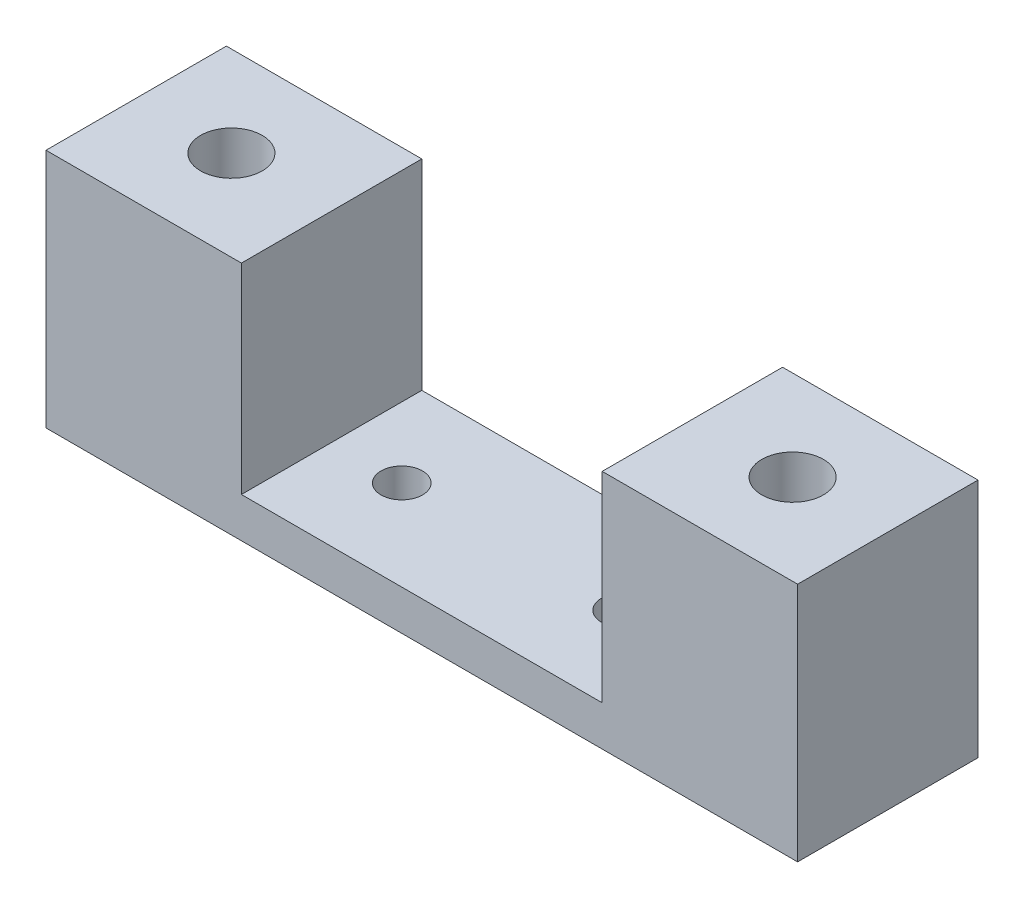
SolidWorks part; units mm, degrees
ref_plane "Front Plane" through (0, 0, 0) normal (0, 0, 1) x (1, 0, 0)
ref_plane "Top Plane" through (0, 0, 0) normal (0, 1, 0) x (1, 0, 0)
ref_plane "Right Plane" through (0, 0, 0) normal (1, 0, 0) x (0, 0, -1)
sketch "Sketch1" plane through (0, 0, 0) normal (0, 1, 0) x (1, 0, 0)
  line L1 (0, 0) -> (75, 0)
  line L2 (0, 0) -> (0, -18)
  line L3 (0, -18) -> (75, -18)
  line L4 (75, 0) -> (75, -18)
  dimension "D1" = 18
  dimension "D2" = 75
extrude "Boss-Extrude1" add sketch "Sketch1" along normal blind 24
sketch "Sketch2" plane through (0, 24, 0) normal (0, 1, 0) x (1, 0, 0)
  line L0 (0, 0) -> (19.5, 0) construction
  line L1 (75, 0) -> (0, 0) construction
  line L2 (0, -18) -> (75, -18) construction
  line L3 (19.5, 0) -> (55.5, 0)
  line L4 (19.5, 0) -> (19.5, -18)
  line L5 (19.5, -18) -> (55.5, -18)
  line L6 (55.5, 0) -> (55.5, -18)
  dimension "D1" = 19.5
  dimension "D2" = 36
extrude "Cut-Extrude1" cut sketch "Sketch2" against normal blind 20
sketch "Sketch3" plane through (0, 4, 0) normal (0, 1, 0) x (1, 0, 0)
  line L0 (19.5, -9) -> (26.5, -9) construction
  line L1 (19.5, 0) -> (19.5, -18) construction
  line L2 (37.5, 0) -> (37.5, -18) construction
  line L3 (55.5, 0) -> (19.5, 0) construction
  line L4 (19.5, -18) -> (55.5, -18) construction
  circle A0 centre (26.5, -9) radius 2.075
  circle A1 centre (48.5, -9) radius 2.075
  dimension "D2" = 4.15
  dimension "D1" = 7
extrude "Cut-Extrude2" cut sketch "Sketch3" against normal up to next
sketch "Sketch4" plane through (0, 24, 0) normal (0, 1, 0) x (1, 0, 0)
  line L0 (0, -9) -> (9.5, -9) construction
  line L1 (0, 0) -> (0, -18) construction
  line L2 (37.5, 0) -> (37.5, -18) construction
  line L3 (55.5, 0) -> (19.5, 0) construction
  line L4 (19.5, -18) -> (55.5, -18) construction
  circle A0 centre (9.5, -9) radius 3.075
  circle A1 centre (65.5, -9) radius 3.075
  dimension "D2" = 6.15
  dimension "D1" = 9.5
extrude "Cut-Extrude4" cut sketch "Sketch4" against normal up to next
sketch "Sketch5" plane through (0, 0, 0) normal (0, -1, 0) x (1, 0, 0)
  line L0 (0, 0) -> (0, 18) construction
  line L1 (14.5, 11.8868) -> (9.5, 14.7735)
  line L2 (9.5, 14.7735) -> (4.5, 11.8868)
  line L3 (4.5, 11.8868) -> (4.5, 6.1132)
  line L4 (4.5, 6.1132) -> (9.5, 3.2265)
  line L5 (9.5, 3.2265) -> (14.5, 6.1132)
  line L6 (14.5, 6.1132) -> (14.5, 11.8868)
  line L7 (75, 18) -> (75, 0) construction
  line L8 (70.5, 6.1132) -> (70.5, 11.8868)
  line L9 (70.5, 11.8868) -> (65.5, 14.7735)
  line L10 (65.5, 14.7735) -> (60.5, 11.8868)
  line L11 (60.5, 11.8868) -> (60.5, 6.1132)
  line L12 (60.5, 6.1132) -> (65.5, 3.2265)
  line L13 (65.5, 3.2265) -> (70.5, 6.1132)
  circle A0 centre (9.5, 9) radius 5 construction
  circle A1 centre (65.5, 9) radius 5 construction
  dimension "D1" = 10
  dimension "D2" = 10
extrude "Cut-Extrude5" cut sketch "Sketch5" against normal blind 5
